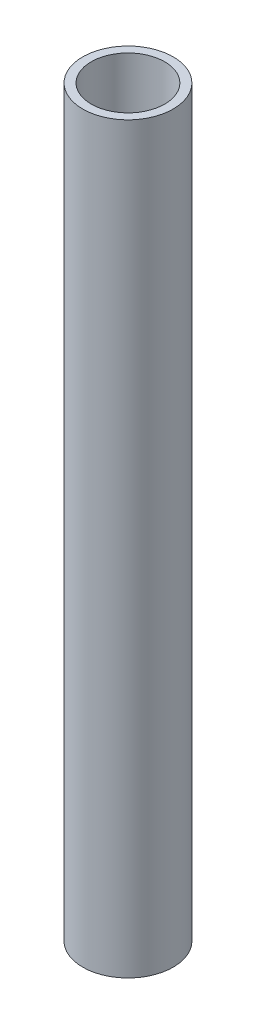
SolidWorks part; units mm, degrees
material "СТ3КП"
ref_plane "Спереди" through (0, 0, 0) normal (0, 0, 1) x (1, 0, 0)
ref_plane "Сверху" through (0, 0, 0) normal (0, 1, 0) x (1, 0, 0)
ref_plane "Справа" through (0, 0, 0) normal (1, 0, 0) x (0, 0, -1)
sketch "Эскиз1" plane through (0, 0, 0) normal (0, 1, 0) x (1, 0, 0)
  line L0 (0, 200914.2922) -> (0, -249007.8193) construction
  line L1 (-95, 9.15) -> (95, 9.15) construction
  circle B0 centre (0, -1.5) radius 8.65
  circle B1 centre (0, -1.5) radius 10.65
sketch_block_instance "Труба 21_3х2 1_2-1"
sketch_block "Труба 21_3х2 1_2" parameters "D2"=21.3, "D1"=2
extrude "Бобышка-Вытянуть1" add sketch "Эскиз1" along normal up to vertex (175 mm away)
